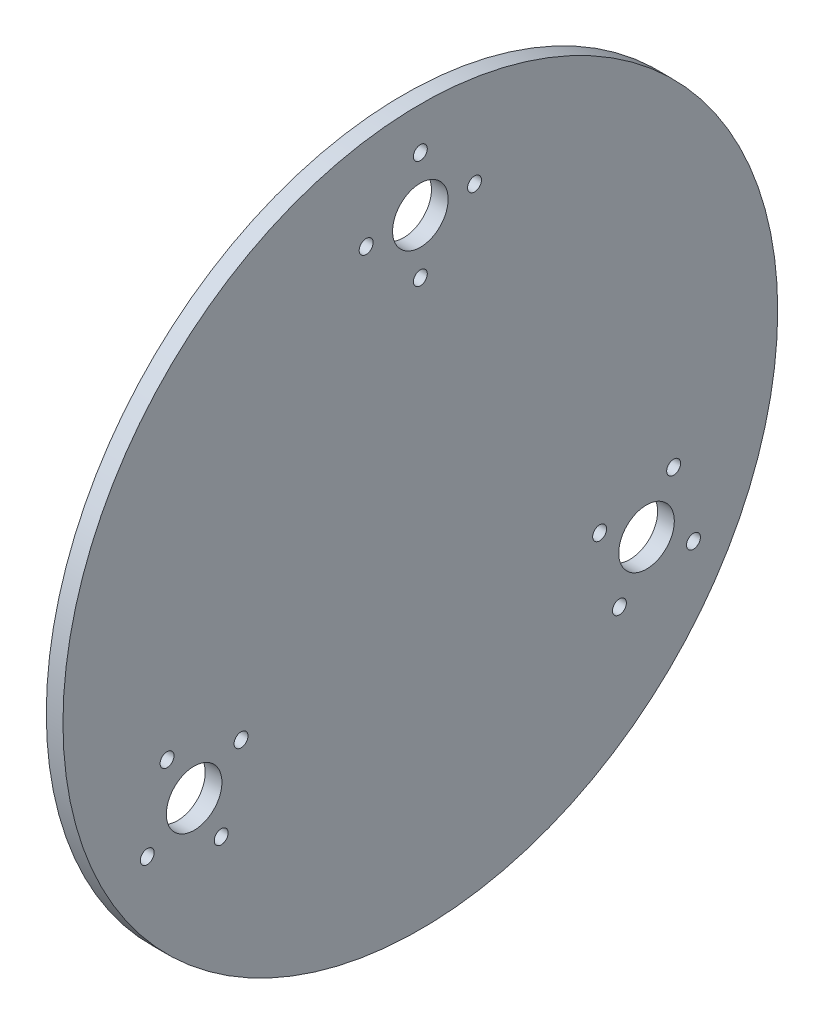
SolidWorks part; units mm, degrees
material "Balsa"
ref_plane "Front Plane" through (0, 0, 0) normal (0, 0, 1) x (1, 0, 0)
ref_plane "Top Plane" through (0, 0, 0) normal (0, 1, 0) x (1, 0, 0)
ref_plane "Right Plane" through (0, 0, 0) normal (1, 0, 0) x (0, 0, -1)
sketch "Sketch1" plane through (0, 0, 0) normal (1, 0, 0) x (0, 0, -1)
  line L0 (-72.7, 0) -> (72.7, 0) construction
  line L1 (-9.75, 47) -> (9.75, 47) construction
  line L2 (0, 37.25) -> (0, 56.75) construction
  circle A0 centre (49.1469, -28.375) radius 1.25
  circle A1 centre (0, 47) radius 5
  circle A2 centre (45.5782, -15.0563) radius 1.25
  circle A3 centre (40.7032, -23.5) radius 5
  circle A4 centre (0, 0) radius 64.3086
  circle A5 centre (0, 56.75) radius 1.25
  circle A6 centre (9.75, 47) radius 1.25
  circle A7 centre (0, 37.25) radius 1.25
  circle A8 centre (-9.75, 47) radius 1.25
  circle A9 centre (35.8282, -31.9437) radius 1.25
  circle A10 centre (32.2594, -18.625) radius 1.25
  circle A11 centre (-49.1469, -28.375) radius 1.25
  circle A12 centre (-35.8282, -31.9437) radius 1.25
  circle A13 centre (-40.7032, -23.5) radius 5
  circle A14 centre (-45.5782, -15.0563) radius 1.25
  circle A15 centre (-32.2594, -18.625) radius 1.25
  point P11 (0, 0)
  point P24 (0, 48.85)
  point P39 (0, 0)
  dimension "D1" = 47
  dimension "D3" = 19.5
  dimension "D4" = 10
  dimension "D5" = 2.5
  dimension "D2" = 3
extrude "Boss-Extrude2" add sketch "Sketch1" along normal blind 3
